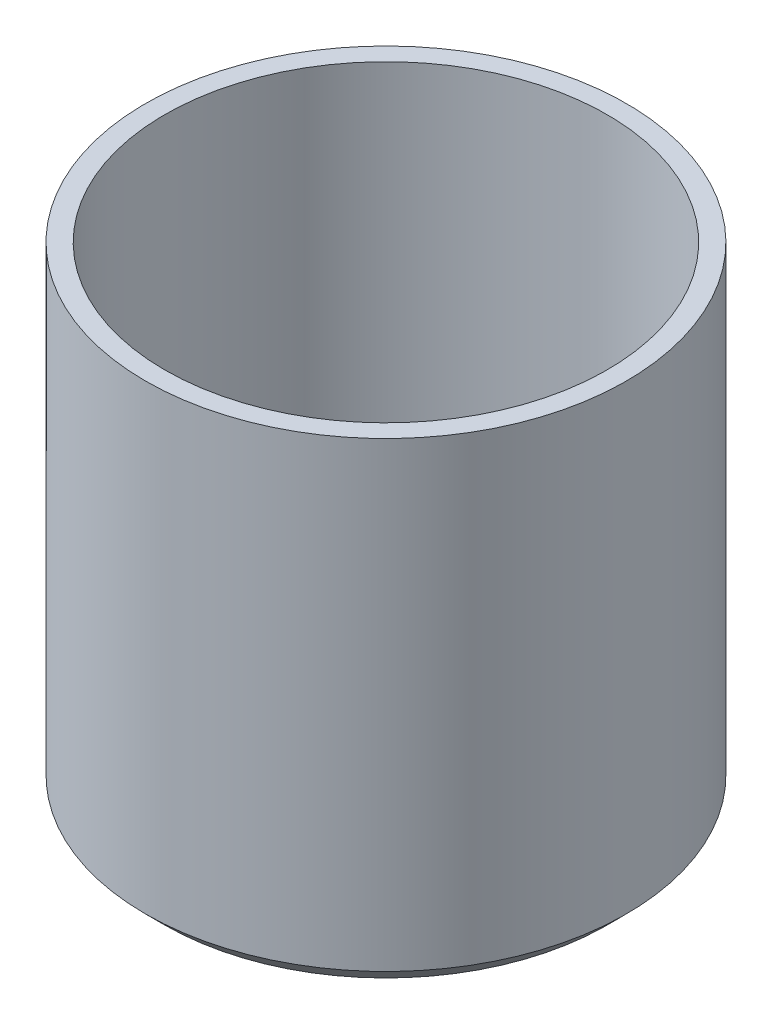
SolidWorks part; units mm, degrees
ref_plane "Front Plane" through (0, 0, 0) normal (0, 0, 1) x (1, 0, 0)
ref_plane "Top Plane" through (0, 0, 0) normal (0, 1, 0) x (1, 0, 0)
ref_plane "Right Plane" through (0, 0, 0) normal (1, 0, 0) x (0, 0, -1)
sketch "Sketch1" plane through (0, 0, 0) normal (0, 1, 0) x (1, 0, 0)
  circle A0 centre (0, 0) radius 12.5
  dimension "D1" = 25
extrude "Boss-Extrude1" add sketch "Sketch1" along normal blind 25
sketch "Sketch2" plane through (0, 25, 0) normal (0, 1, 0) x (1, 0, 0)
  circle A0 centre (0, 0) radius 11.5
  circle A2 centre (0, 0) radius 12.5 construction
  dimension "D1" = 1
extrude "Cut-Extrude1" cut sketch "Sketch2" against normal offset from surface (24 mm away) 1 up to face at (0, 0, 12.5)
sketch "Sketch3" plane through (0, 0, 0) normal (0, -1, 0) x (1, 0, 0)
  circle A0 centre (0, 0) radius 1
  circle A1 centre (4, 0) radius 1
  circle A2 centre (8, 0) radius 1
  circle A3 centre (0, 0) radius 1
  circle A4 centre (2.8284, -2.8284) radius 1
  circle A5 centre (5.6569, -5.6569) radius 1
  circle A6 centre (0, 0) radius 1
  circle A7 centre (0, -4) radius 1
  circle A8 centre (0, -8) radius 1
  circle A9 centre (0, 0) radius 1
  circle A10 centre (-2.8284, -2.8284) radius 1
  circle A11 centre (-5.6569, -5.6569) radius 1
  circle A12 centre (0, 0) radius 1
  circle A13 centre (-4, 0) radius 1
  circle A14 centre (-8, 0) radius 1
  circle A15 centre (0, 0) radius 1
  circle A16 centre (-2.8284, 2.8284) radius 1
  circle A17 centre (-5.6569, 5.6569) radius 1
  circle A18 centre (0, 0) radius 1
  circle A19 centre (0, 4) radius 1
  circle A20 centre (0, 8) radius 1
  circle A21 centre (0, 0) radius 1
  circle A22 centre (2.8284, 2.8284) radius 1
  circle A23 centre (5.6569, 5.6569) radius 1
  point P45 (0, 0)
  dimension "D1" = 2
  dimension "D4" = 4
  dimension "D2" = 3
  dimension "D3" = 8
extrude "Cut-Extrude2" cut sketch "Sketch3" against normal up to next contours A0 | A16 | A17 | A20 | A19 | A22 | A23 | A2 | A1 | A4 | A5 | A7 | A10 | A13 | A14 | A11 | A8
chamfer "Chamfer1" distance 1 angle 45 2 edges at (0, 1, 11.5) (0, 0, 12.5)
